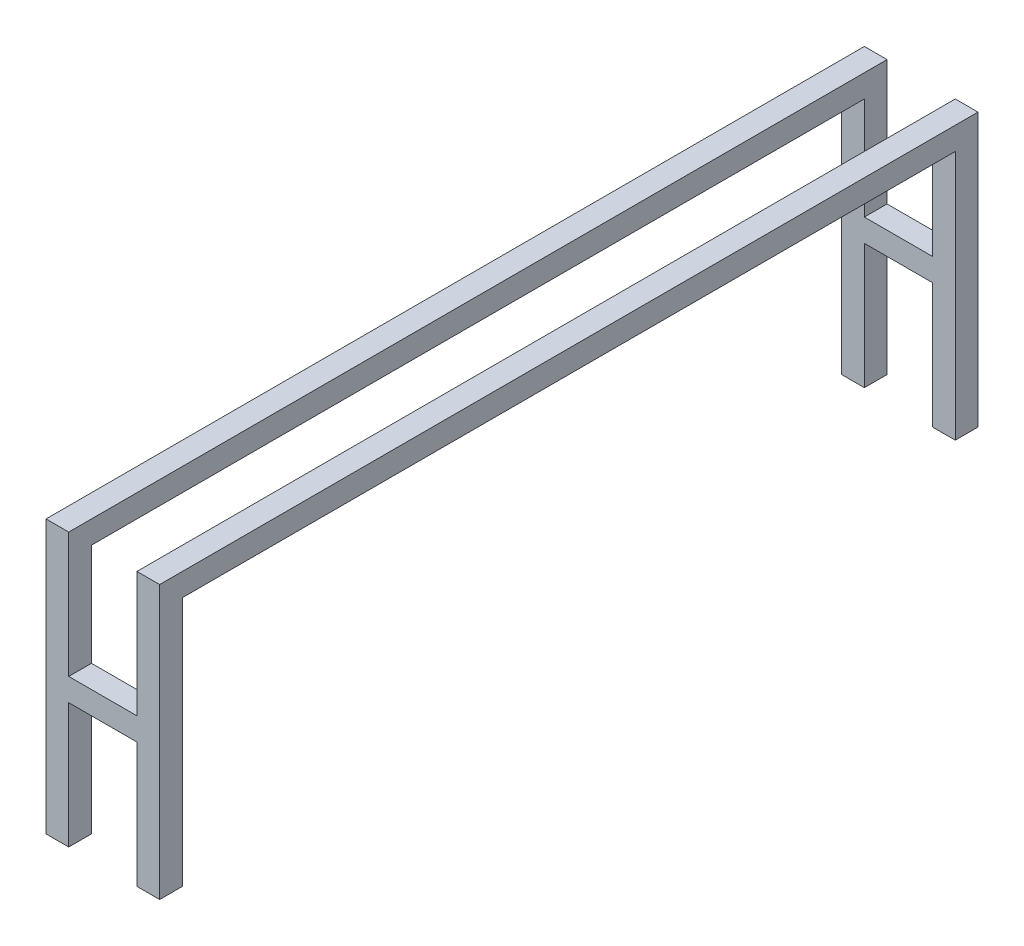
SolidWorks part; units mm, degrees
ref_plane "Alzado" through (0, 0, 0) normal (0, 0, 1) x (1, 0, 0)
ref_plane "Planta" through (0, 0, 0) normal (0, 1, 0) x (1, 0, 0)
ref_plane "Vista lateral" through (0, 0, 0) normal (1, 0, 0) x (0, 0, -1)
sketch "Croquis1" plane through (0, 0, 0) normal (1, 0, 0) x (0, 0, -1)
  line L0 (0, 0) -> (0, 600)
  line L1 (0, 600) -> (-1800, 600)
  line L2 (-1800, 600) -> (-1800, 0)
  line L3 (-50, 0) -> (-50, 550)
  line L4 (-50, 550) -> (-1750, 550)
  line L5 (-1750, 550) -> (-1750, 0)
  line L6 (-1800, 0) -> (-1750, 0)
  line L7 (-50, 0) -> (0, 0)
  dimension "D2" = 600
  dimension "D3" = 1800
  dimension "D4" = 600
  dimension "D1" = 50
extrude "Saliente-Extruir1" add sketch "Croquis1" along normal blind 50
sketch "Croquis2" plane through (0, 0, 0) normal (-1, 0, 0) x (0, 0, 1)
  line L0 (1800, 600) -> (1800, 0) construction
  line L1 (1800, 275) -> (1750, 275)
  line L2 (1800, 275) -> (1800, 325)
  line L3 (1800, 325) -> (1750, 325)
  line L4 (1750, 275) -> (1750, 325)
  line L5 (1750, 0) -> (1750, 550) construction
  line L6 (1800, 0) -> (1750, 0) construction
  line L7 (900, 600) -> (900, 0) construction
  line L8 (0, 600) -> (1800, 600) construction
  line L9 (50, 275) -> (50, 325)
  line L10 (0, 325) -> (50, 325)
  line L11 (0, 275) -> (0, 325)
  line L12 (0, 275) -> (50, 275)
  dimension "D1" = 50
  dimension "D2" = 275
extrude "Saliente-Extruir2" add sketch "Croquis2" along normal blind 150
sketch "Croquis3" plane through (-150, 0, 0) normal (-1, 0, 0) x (0, 0, 1)
  line L0 (1750, 0) -> (1800, 0)
  line L1 (0, 0) -> (50, 0)
  line L2 (0, 0) -> (0, 600)
  line L3 (0, 600) -> (1800, 600)
  line L4 (1800, 0) -> (1800, 600)
  line L6 (50, 0) -> (50, 550)
  line L7 (50, 550) -> (1750, 550)
  line L8 (1750, 0) -> (1750, 550)
extrude "Saliente-Extruir3" add sketch "Croquis3" along normal blind 50
